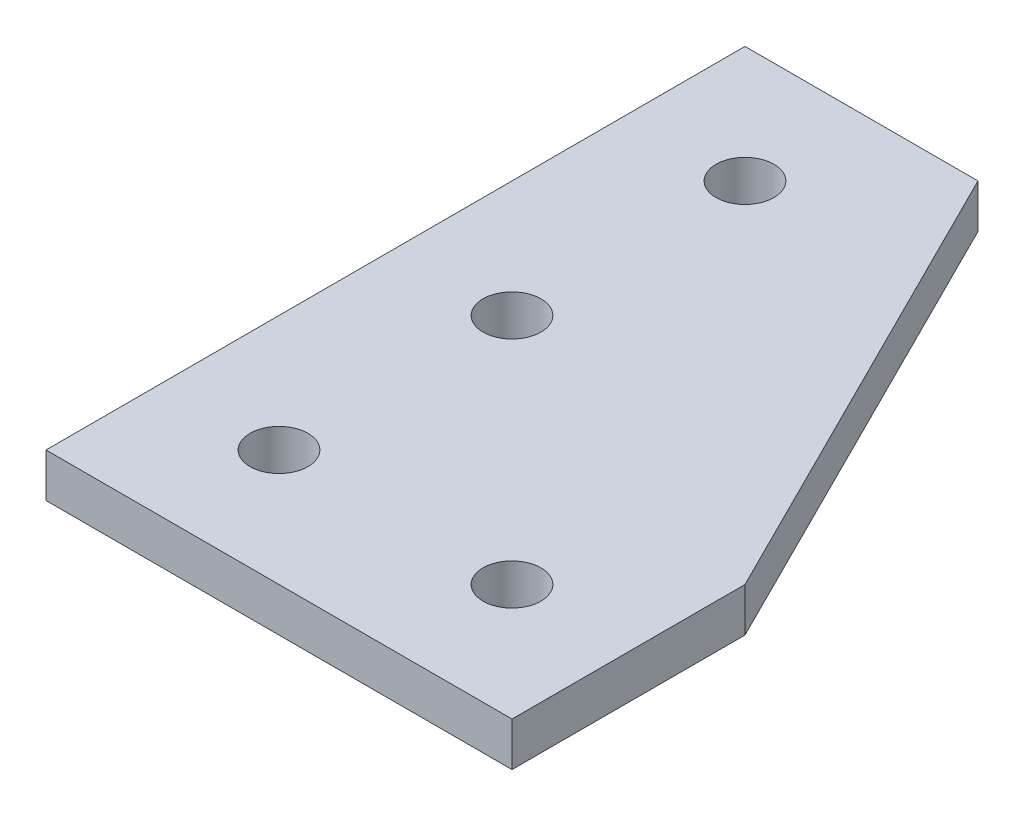
SolidWorks part; units mm, degrees
material "6105-T5 Aluminum"
ref_plane "Front Plane" through (0, 0, 0) normal (0, 0, 1) x (1, 0, 0)
ref_plane "Top Plane" through (0, 0, 0) normal (0, 1, 0) x (1, 0, 0)
ref_plane "Right Plane" through (0, 0, 0) normal (1, 0, 0) x (0, 0, -1)
sketch "Sketch1" plane through (0, 0, 0) normal (0, 0, 1) x (1, 0, 0)
  line L1 (-25.4, -2.3876) -> (25.4, -2.3876)
  line L2 (-25.4, -2.3876) -> (-25.4, 2.3876)
  line L3 (-25.4, 2.3876) -> (25.4, 2.3876)
  line L4 (25.4, -2.3876) -> (25.4, 2.3876)
  line L5 (-25.4, -2.3876) -> (25.4, 2.3876) construction
  line L6 (-25.4, 2.3876) -> (25.4, -2.3876) construction
  point P0 (0, 0)
  dimension "D1" = 50.8
  dimension "D2" = 4.7752
extrude "Boss-Extrude1" add sketch "Sketch1" along normal mid plane 76.2
sketch "Sketch8" plane through (0, 2.3876, 0) normal (0, 1, 0) x (-1, 0, 0)
  line L0 (0, -38.1) -> (-25.4, 12.7)
  line L1 (-25.4, -38.1) -> (25.4, -38.1) construction
  line L2 (-25.4, 38.1) -> (-25.4, -38.1) construction
  line L3 (-25.4, 12.7) -> (-25.4, -38.1)
  line L4 (-25.4, -38.1) -> (0, -38.1)
  line L5 (-25.4, 38.1) -> (25.4, 38.1) construction
  line L6 (25.4, 38.1) -> (25.4, -38.1) construction
  dimension "D1" = 25.4
  dimension "D2" = 25.4
extrude "Cut-Extrude2" cut sketch "Sketch8" against normal blind 7.62
sketch "Sketch9" plane through (0, 2.3876, 0) normal (0, 1, 0) x (1, 0, 0)
  circle A0 centre (-12.7, 25.4) radius 3.1519
  dimension "D1" = 25.4
  dimension "D2" = 12.7
extrude "Cut-Extrude3" cut sketch "Sketch9" against normal through all
pattern_linear "LPattern1" count 3 spacing 25.4 along (0, 0, 1) count 2 spacing 25.4 along (1, 0, 0) skipping (0, 1), (1, 1) of "Cut-Extrude3"
